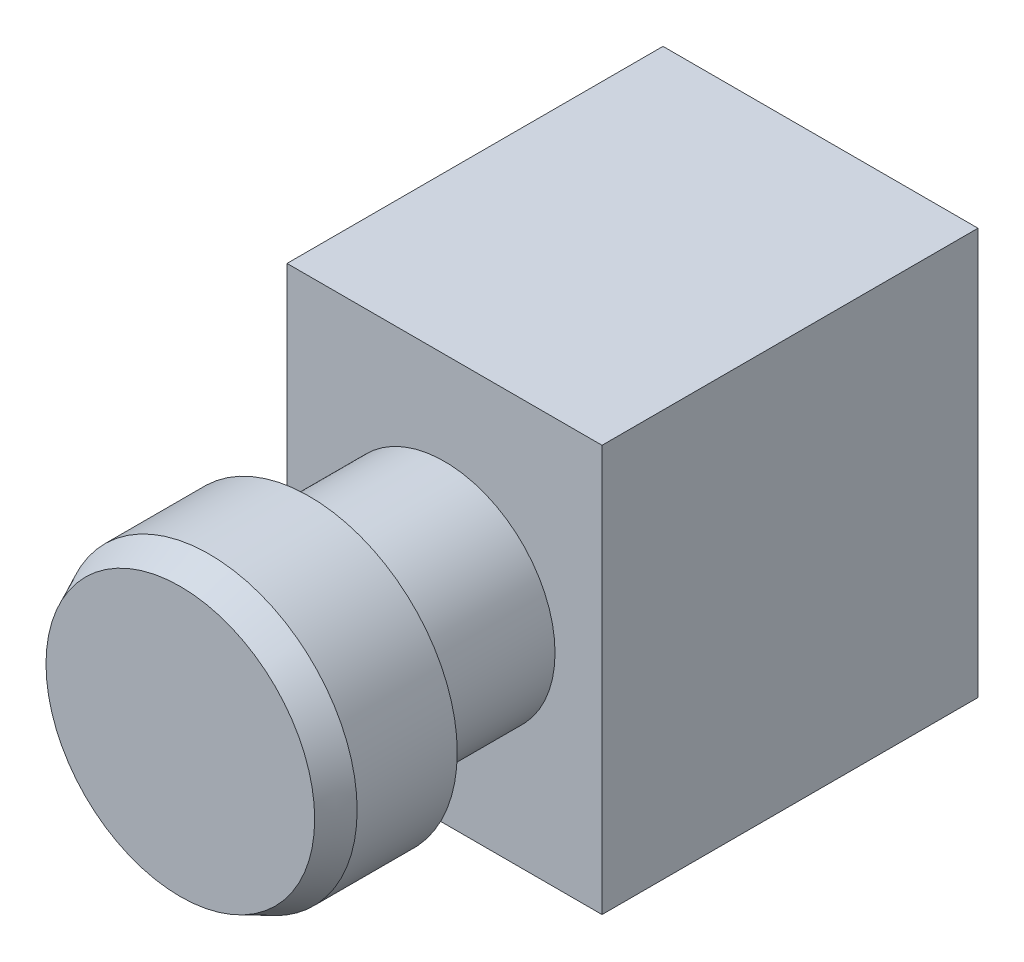
SolidWorks part; units mm, degrees
ref_plane "Front" through (0, 0, 0) normal (0, 0, 1) x (1, 0, 0)
ref_plane "Top" through (0, 0, 0) normal (0, 1, 0) x (1, 0, 0)
ref_plane "Right" through (0, 0, 0) normal (1, 0, 0) x (0, 0, -1)
sketch "Sketch1" plane through (0, 0, 0) normal (0, 0, 1) x (1, 0, 0)
  circle A0 centre (0, 0) radius 14.55
  dimension "D1" = 29.1
extrude "Boss-Extrude1" add sketch "Sketch1" along normal blind 9.85
sketch "Sketch3" plane through (0, 0, 9.85) normal (0, 0, 1) x (1, 0, 0)
  circle A1 centre (0, 0) radius 14.55
  circle A2 centre (0, 0) radius 14.55
  dimension "D1" = 0
extrude "Boss-Extrude3" add sketch "Sketch3" along normal blind 2.85 draft 25
sketch "Sketch4" plane through (0, 0, 0) normal (0, 0, 1) x (1, 0, 0)
  circle A0 centre (0, 0) radius 10.875
  dimension "D1" = 21.75
extrude "Boss-Extrude4" add sketch "Sketch4" against normal blind 13.3
sketch "Sketch2" plane through (0, 0, -13.3) normal (0, 0, 1) x (1, 0, 0)
  line L1 (-15.5, -20) -> (15.5, -20)
  line L2 (-15.5, -20) -> (-15.5, 20)
  line L3 (-15.5, 20) -> (15.5, 20)
  line L4 (15.5, -20) -> (15.5, 20)
  line L5 (-15.5, -20) -> (15.5, 20) construction
  line L6 (-15.5, 20) -> (15.5, -20) construction
  point P0 (0, 0)
  dimension "D1" = 31
  dimension "D2" = 40
extrude "Boss-Extrude2" add sketch "Sketch2" against normal blind 37
sketch "Panel Cut Guide" plane through (0, 0, 0) normal (0, 0, 1) x (1, 0, 0)
  line L0 (-10.15, 4.24) -> (-10.15, -4.24)
  line L1 (10.15, 4.24) -> (10.15, -4.24)
  line L2 (0, 11) -> (0, 0) construction
  circle A0 centre (0, 0) radius 11 construction
  arc A1 (-10.15, 4.24) -> (10.15, 4.24) centre (0, 0) cw
  arc A2 (10.15, -4.24) -> (-10.15, -4.24) centre (0, 0) cw
  dimension "D1" = 22
  dimension "D2" = 20.3
